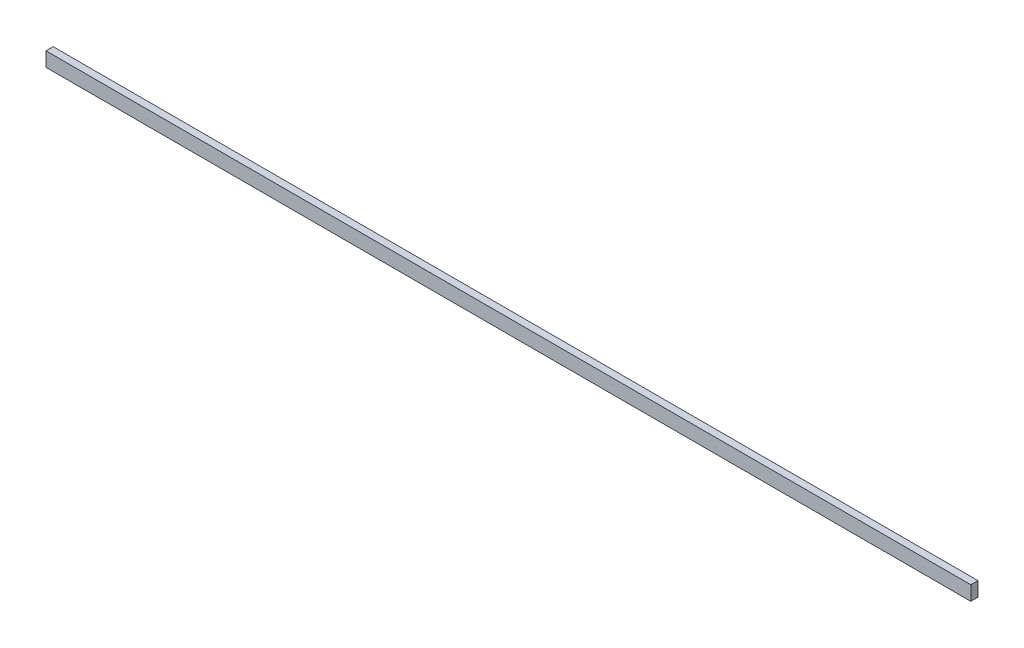
SolidWorks part; units mm, degrees
material "Caoba"
ref_plane "Alzado" through (0, 0, 0) normal (0, 0, 1) x (1, 0, 0)
ref_plane "Planta" through (0, 0, 0) normal (0, 1, 0) x (1, 0, 0)
ref_plane "Vista lateral" through (0, 0, 0) normal (1, 0, 0) x (0, 0, -1)
sketch "Croquis1" plane through (0, 0, 0) normal (1, 0, 0) x (0, 0, -1)
  line L1 (2.5, 5) -> (-2.5, 5)
  line L2 (2.5, 5) -> (2.5, -5)
  line L3 (2.5, -5) -> (-2.5, -5)
  line L4 (-2.5, 5) -> (-2.5, -5)
  line L5 (2.5, 5) -> (-2.5, -5) construction
  line L6 (2.5, -5) -> (-2.5, 5) construction
  point P0 (0, 0)
  dimension "D1" = 5
  dimension "D2" = 10
extrude "Saliente-Extruir1" add sketch "Croquis1" along normal blind 645
